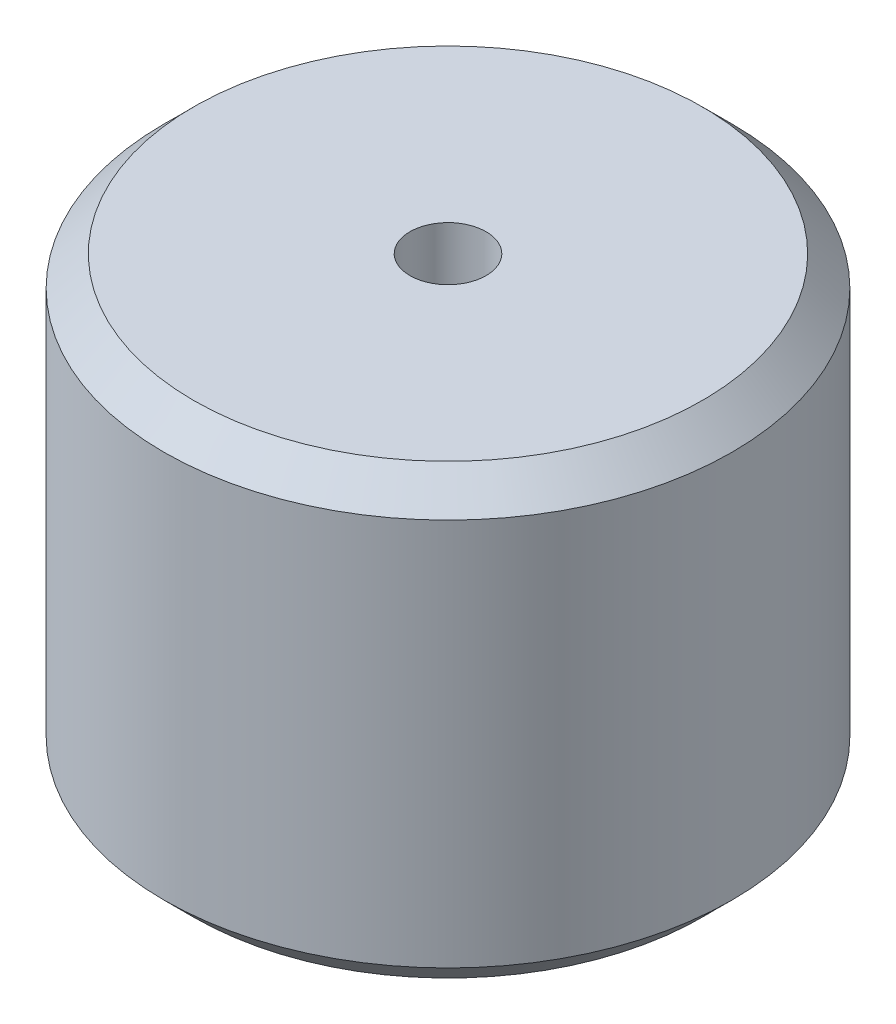
SolidWorks part; units mm, degrees
material "AISI 1020"
ref_plane "Alzado" through (0, 0, 0) normal (0, 0, 1) x (1, 0, 0)
ref_plane "Planta" through (0, 0, 0) normal (0, 1, 0) x (1, 0, 0)
ref_plane "Vista lateral" through (0, 0, 0) normal (1, 0, 0) x (0, 0, -1)
sketch "Croquis1" plane through (0, 0, 0) normal (0, 1, 0) x (1, 0, 0)
  circle A0 centre (0, 0) radius 19.05
  dimension "D1" = 38.1
extrude "Saliente-Extruir1" add sketch "Croquis1" along normal blind 30
chamfer "Chaflán1" distance 2 angle 45 1 edges at (0, 30, 19.05)
hole_wizard "Taladro roscado 1/4-201" positions "Croquis2" profile "Croquis3" tap size "1/4-20" standard "Ansi Inch"
sketch "Croquis2" plane through (0, 30, 0) normal (0, 1, 0) x (1, 0, 0)
  point P0 (0, 0)
sketch "Croquis3" plane through (0, 30, 0) normal (1, 0, 0) x (0, 0, 1)
  line L0 (0, 0) -> (0, 26.5338)
  line L1 (0, 26.5338) -> (2.5527, 25)
  line L2 (2.5527, 25) -> (2.5527, 0)
  line L5 (2.5527, 0) -> (0, 0)
  line L10 (0, 26.5338) -> (-2.5527, 25) construction
  line L11 (0, -6.35) -> (0, 107.95) construction
  dimension "Diámetro de perforador para roscar" = 5.1054
  dimension "Profundidad de perforador para roscar" = 25
  dimension "Ángulo de perforador" = 118
cosmetic thread "Rosca de taladro1"
chamfer "Chaflán2" distance 2 angle 45 1 edges at (0, 0, 19.05)
